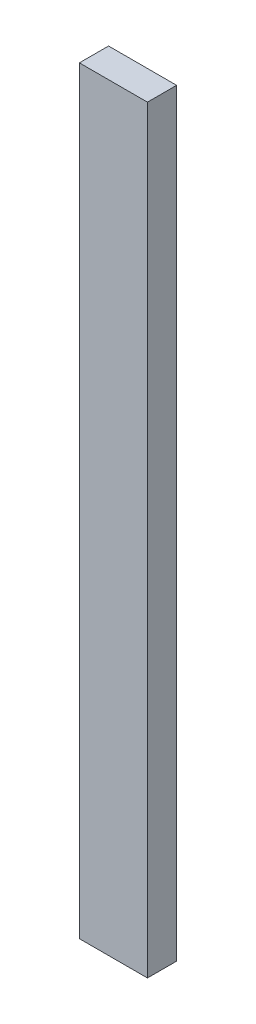
SolidWorks part; units mm, degrees
ref_plane "Front Plane" through (0, 0, 0) normal (0, 0, 1) x (1, 0, 0)
ref_plane "Top Plane" through (0, 0, 0) normal (0, 1, 0) x (1, 0, 0)
ref_plane "Right Plane" through (0, 0, 0) normal (1, 0, 0) x (0, 0, -1)
sketch "Sketch1" plane through (0, 0, 0) normal (0, 1, 0) x (1, 0, 0)
  line L1 (-44.45, -19.05) -> (44.45, -19.05)
  line L2 (-44.45, -19.05) -> (-44.45, 19.05)
  line L3 (-44.45, 19.05) -> (44.45, 19.05)
  line L4 (44.45, -19.05) -> (44.45, 19.05)
  line L5 (-44.45, -19.05) -> (44.45, 19.05) construction
  line L6 (-44.45, 19.05) -> (44.45, -19.05) construction
  point P0 (0, 0)
  dimension "D1" = 88.9
  dimension "D2" = 38.1
extrude "Boss-Extrude1" add sketch "Sketch1" along normal blind 990.6
